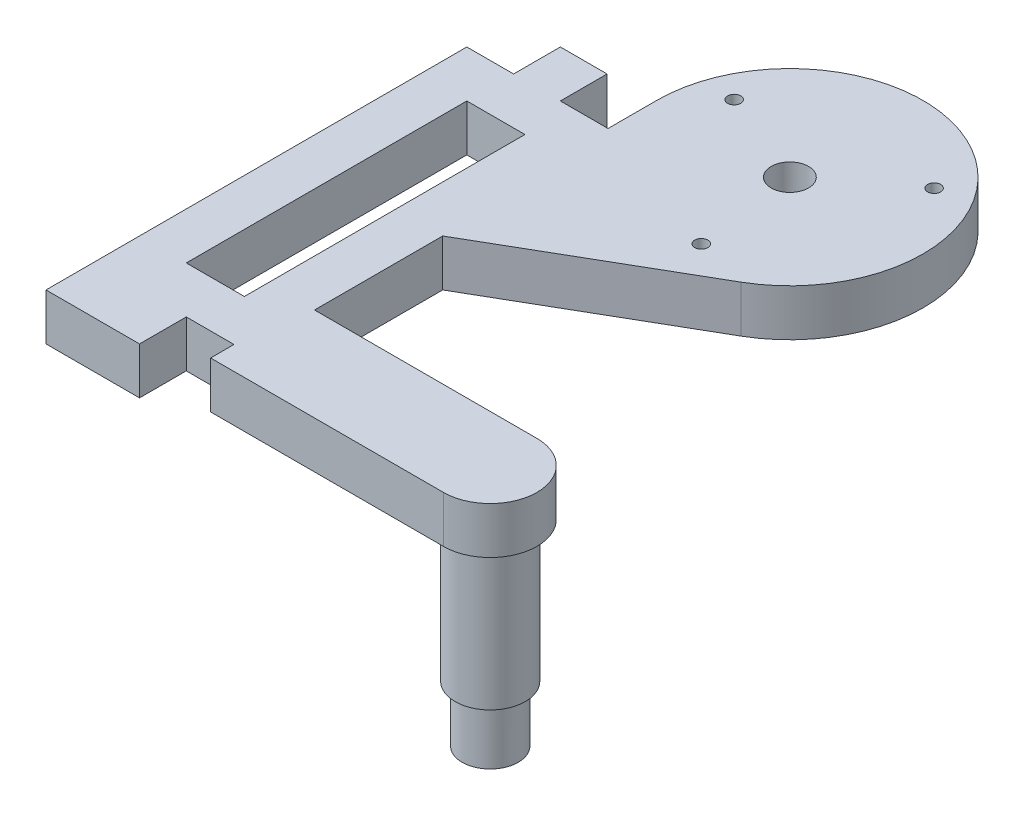
SolidWorks part; units mm, degrees
ref_plane "Front Plane" through (0, 0, 0) normal (0, 0, 1) x (1, 0, 0)
ref_plane "Top Plane" through (0, 0, 0) normal (0, 1, 0) x (1, 0, 0)
ref_plane "Right Plane" through (0, 0, 0) normal (1, 0, 0) x (0, 0, -1)
sketch "Sketch1" plane through (0, 0, 0) normal (0, 1, 0) x (1, 0, 0)
  line L1 (0, 0) -> (45, 0)
  line L2 (0, 0) -> (0, 12)
  line L3 (0, 12) -> (45, 12)
  line L5 (0, 0) -> (15, 0)
  line L6 (0, 0) -> (0, -5)
  line L7 (0, -5) -> (15, -5)
  line L8 (15, 0) -> (15, -5)
  line L9 (0, 12) -> (24, 12)
  line L10 (0, 12) -> (0, 55.0692)
  line L11 (0, 55.0692) -> (24, 55.0692)
  line L12 (24, 12) -> (24, 55.0692)
  circle A0 centre (45, 6) radius 3
  arc A1 (45, 0) -> (45, 12) centre (45, 6) ccw
  circle A6 centre (12, 53.0692) radius 0.7
  circle A7 centre (21.5263, 36.5692) radius 0.7
  circle A8 centre (2.4737, 36.5692) radius 0.7
  circle A11 centre (12, 42.0692) radius 2
  dimension "D4" = 45
  dimension "D3" = 6
  dimension "D11" = 1.4
  dimension "D1" = 5
  dimension "D2" = 15
  dimension "D5" = 6
  dimension "D13" = 3
sketch "Sketch2" plane through (0, 0, 0) normal (0, 1, 0) x (1, 0, 0)
  line L0 (15.1, 45.212) -> (15.1, 40)
  line L1 (0, 0) -> (15, 0)
  line L5 (0, 0) -> (15.1, 0)
  line L6 (0, 0) -> (0, 40)
  line L7 (0, 40) -> (16.2133, 40)
  line L8 (16.2133, 7.5) -> (16.2133, 40)
  line L9 (10, 40) -> (5, 40)
  line L10 (10, 40) -> (10, 45)
  line L11 (10, 45) -> (5, 45)
  line L12 (5, 40) -> (5, 45)
  line L17 (14.5855, 20.2678) -> (36.4451, 32.8884)
  line L18 (36.4451, 32.8884) -> (16.2133, 21.2076)
  line L19 (29.3301, 45.212) -> (38.057, 51.9084) construction
  line L20 (16.2133, 7.5) -> (40, 7.5)
  line L21 (15.1, 0) -> (15.1, -2.5)
  line L22 (15.1, -2.5) -> (40, -2.5)
  line L25 (5, 35) -> (11.2133, 35)
  line L26 (5, 35) -> (5, 5)
  line L27 (5, 5) -> (11.2133, 5)
  line L28 (11.2133, 35) -> (11.2133, 5)
  line L29 (0, 0) -> (10, 0)
  line L30 (0, 0) -> (0, -5)
  line L31 (0, -5) -> (10, -5)
  line L32 (10, 0) -> (10, -5)
  circle A10 centre (29.3301, 45.212) radius 14.2301
  circle A11 centre (29.3301, 45.212) radius 2
  circle A12 centre (40, 2.5) radius 39.7 construction
  circle A13 centre (29.3301, 45.212) radius 4.3246 construction
  arc A14 (40, -2.5) -> (40, 7.5) centre (40, 2.5) ccw
  circle A15 centre (38.057, 51.9084) radius 0.7
  circle A18 centre (30.7659, 34.3061) radius 0.7
  circle A19 centre (19.1674, 49.4216) radius 0.7
  point P39 (5, 42.5)
  dimension "D5" = 79.4
  dimension "D6" = 40
  dimension "D7" = 5.1
  dimension "D8" = 2.5
  dimension "D9" = 60
  dimension "D10" = 5
  dimension "D14" = 52.5
  dimension "D1" = 40
  dimension "D2" = 5
  dimension "D3" = 5
  dimension "D4" = 10
  dimension "D11" = 5
  dimension "D12" = 11
  dimension "D13" = 5
  dimension "D16" = 5
  dimension "D17" = 5
  dimension "D18" = 5
  dimension "D19" = 5
  dimension "D20" = 5.1
  dimension "D21" = 5
  dimension "D15" = 3
extrude "Boss-Extrude1" add sketch "Sketch2" along normal blind 5
sketch "Sketch3" plane through (0, 5, 0) normal (0, 1, 0) x (1, 0, 0)
  circle A0 centre (40, 2.5) radius 3.75
extrude "Boss-Extrude2" add sketch "Sketch3" against normal blind 20
sketch "Sketch4" plane through (0, -15, 0) normal (0, -1, 0) x (-1, 0, 0)
  circle A0 centre (-40, 2.5) radius 3
  circle A1 centre (-40, 2.5) radius 1.75
extrude "Boss-Extrude3" add sketch "Sketch4" along normal blind 6
